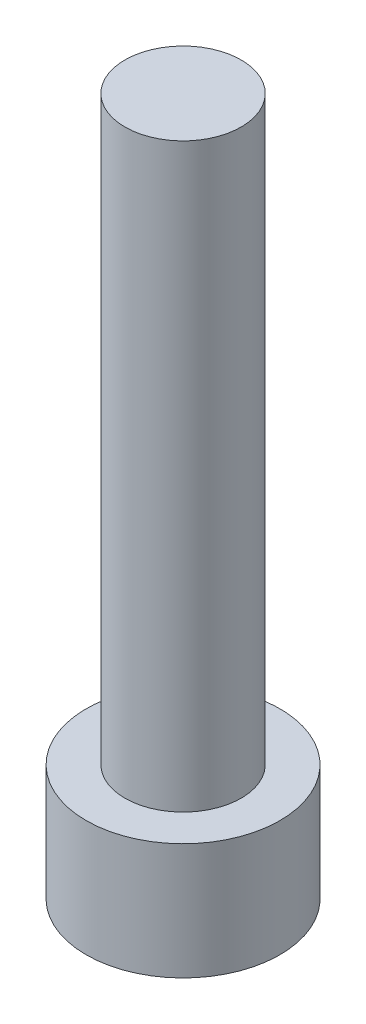
SolidWorks part; units mm, degrees
ref_plane "前视基准面" through (0, 0, 0) normal (0, 0, 1) x (1, 0, 0)
ref_plane "上视基准面" through (0, 0, 0) normal (0, 1, 0) x (1, 0, 0)
ref_plane "右视基准面" through (0, 0, 0) normal (1, 0, 0) x (0, 0, -1)
other "Configuration Table"
sketch "草图1" plane through (0, 0, 0) normal (0, 1, 0) x (1, 0, 0)
  circle A0 centre (0, 0) radius 5
  dimension "D1" = 10
extrude "凸台-拉伸1" add sketch "草图1" along normal blind 6
sketch "草图2" plane through (0, 0, 0) normal (0, 1, 0) x (1, 0, 0)
  circle A0 centre (0, 0) radius 3
  dimension "D1" = 6
extrude "凸台-拉伸2" add sketch "草图2" along normal blind 30 from surface at 6 starting at face at (0, 6, 5)
sketch "草图4" plane through (0, 0, 0) normal (0, 1, 0) x (1, 0, 0)
  line L1 (2.8868, 0) -> (1.4434, 2.5)
  line L2 (1.4434, 2.5) -> (-1.4434, 2.5)
  line L3 (-1.4434, 2.5) -> (-2.8868, 0)
  line L4 (-2.8868, 0) -> (-1.4434, -2.5)
  line L5 (-1.4434, -2.5) -> (1.4434, -2.5)
  line L6 (1.4434, -2.5) -> (2.8868, 0)
  circle A0 centre (0, 0) radius 2.5 construction
  dimension "D1" = 5
extrude "切除-拉伸1" cut sketch "草图4" along normal blind 3
